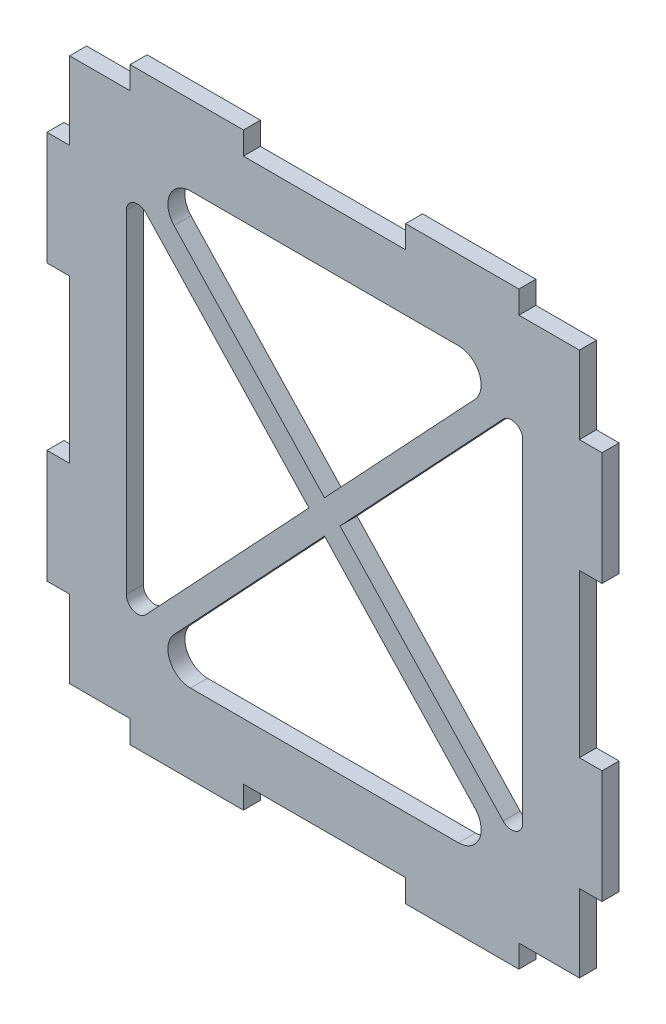
SolidWorks part; units mm, degrees
ref_plane "前视基准面" through (0, 0, 0) normal (0, 0, 1) x (1, 0, 0)
ref_plane "上视基准面" through (0, 0, 0) normal (0, 1, 0) x (1, 0, 0)
ref_plane "右视基准面" through (0, 0, 0) normal (1, 0, 0) x (0, 0, -1)
other "Configuration Table"
sketch "草图1" plane through (0, 0, 0) normal (0, 0, 1) x (1, 0, 0)
  line L0 (2296.8489, 1260.8998) -> (2286.8489, 1260.8998)
  line L1 (2311.1653, 1260.8998) -> (2321.1653, 1260.8998)
  line L2 (2286.8489, 1258.8998) -> (2281.5071, 1258.8998)
  line L3 (2321.1653, 1258.8998) -> (2326.5071, 1258.8998)
  line L4 (2321.1653, 1260.8998) -> (2321.1653, 1258.8998)
  line L5 (2311.1653, 1260.8998) -> (2311.1653, 1258.8998)
  line L6 (2311.1653, 1258.8998) -> (2296.8489, 1258.8998)
  line L7 (2281.5071, 1242.058) -> (2281.5071, 1227.7416)
  line L8 (2281.5071, 1217.7416) -> (2281.5071, 1210.8998)
  line L9 (2281.5071, 1252.058) -> (2281.5071, 1258.8998)
  line L10 (2326.5071, 1242.058) -> (2326.5071, 1227.7416)
  line L11 (2326.5071, 1217.7416) -> (2326.5071, 1210.8998)
  line L12 (2326.5071, 1252.058) -> (2326.5071, 1258.8998)
  line L13 (2279.5071, 1252.058) -> (2281.5071, 1252.058)
  line L14 (2279.5071, 1242.058) -> (2281.5071, 1242.058)
  line L15 (2279.5071, 1227.7416) -> (2281.5071, 1227.7416)
  line L16 (2279.5071, 1217.7416) -> (2281.5071, 1217.7416)
  line L17 (2281.5071, 1252.058) -> (2279.5071, 1252.058)
  line L18 (2279.5071, 1252.058) -> (2279.5071, 1242.058)
  line L19 (2279.5071, 1227.7416) -> (2279.5071, 1217.7416)
  line L20 (2281.5071, 1258.8998) -> (2286.8489, 1258.8998)
  line L21 (2296.8489, 1258.8998) -> (2304.0071, 1258.8998)
  line L22 (2328.5071, 1252.058) -> (2326.5071, 1252.058)
  line L23 (2328.5071, 1242.058) -> (2326.5071, 1242.058)
  line L24 (2328.5071, 1227.7416) -> (2326.5071, 1227.7416)
  line L25 (2328.5071, 1217.7416) -> (2326.5071, 1217.7416)
  line L26 (2326.5071, 1252.058) -> (2328.5071, 1252.058)
  line L27 (2328.5071, 1252.058) -> (2328.5071, 1242.058)
  line L28 (2328.5071, 1227.7416) -> (2328.5071, 1217.7416)
  line L29 (2281.5071, 1210.8998) -> (2286.8489, 1210.8998)
  line L30 (2296.8489, 1210.8998) -> (2311.1653, 1210.8998)
  line L31 (2321.1653, 1210.8998) -> (2326.5071, 1210.8998)
  line L32 (2296.8489, 1260.8998) -> (2296.8489, 1258.8998)
  line L33 (2286.8489, 1260.8998) -> (2286.8489, 1258.8998)
  line L34 (2321.1653, 1210.8998) -> (2321.1653, 1208.8998)
  line L35 (2311.1653, 1210.8998) -> (2311.1653, 1208.8998)
  line L36 (2296.8489, 1210.8998) -> (2296.8489, 1208.8998)
  line L37 (2286.8489, 1210.8998) -> (2286.8489, 1208.8998)
  line L38 (2286.8489, 1208.8998) -> (2296.8489, 1208.8998)
  line L39 (2311.1653, 1208.8998) -> (2321.1653, 1208.8998)
  line L40 (2321.5071, 1249.6017) -> (2321.5071, 1220.186)
  line L41 (2290.7227, 1250.5319) -> (2304.0071, 1236.3619)
  line L42 (2288.2366, 1250.2595) -> (2302.6364, 1234.8998)
  line L43 (2304.0071, 1233.4377) -> (2317.3358, 1219.2203)
  line L44 (2288.2138, 1219.5157) -> (2302.6364, 1234.8998)
  line L45 (2304.0071, 1236.3619) -> (2317.3215, 1250.564)
  line L46 (2305.3778, 1234.8998) -> (2319.7779, 1250.2591)
  line L47 (2292.1818, 1253.8998) -> (2315.8328, 1253.8995)
  line L48 (2286.5071, 1249.5756) -> (2286.5075, 1220.2235)
  line L49 (2304.0071, 1233.4377) -> (2290.7231, 1219.2673)
  line L50 (2319.7783, 1219.5409) -> (2305.3778, 1234.8998)
  line L51 (2292.1823, 1215.8995) -> (2315.8334, 1215.9004)
  arc A0 (2288.2366, 1250.2595) -> (2286.5071, 1249.5756) centre (2287.5071, 1249.5756) ccw
  arc A1 (2292.1818, 1253.8998) -> (2290.7227, 1250.5319) centre (2292.1818, 1251.8998) ccw
  arc A2 (2321.5074, 1249.5751) -> (2319.7779, 1250.2591) centre (2320.5074, 1249.5752) ccw
  arc A3 (2317.2918, 1250.5316) -> (2315.8328, 1253.8995) centre (2315.8328, 1251.8995) ccw
  arc A4 (2286.5075, 1220.2235) -> (2288.237, 1219.5396) centre (2287.5075, 1220.2236) ccw
  arc A5 (2290.7231, 1219.2673) -> (2292.1823, 1215.8995) centre (2292.1822, 1217.8995) ccw
  arc A6 (2319.7783, 1219.5409) -> (2321.5078, 1220.2249) centre (2320.5078, 1220.2249) ccw
  arc A7 (2315.8334, 1215.9004) -> (2317.2923, 1219.2683) centre (2315.8333, 1217.9004) ccw
extrude "凸台-拉伸1" add sketch "草图1" along normal blind 1.5
